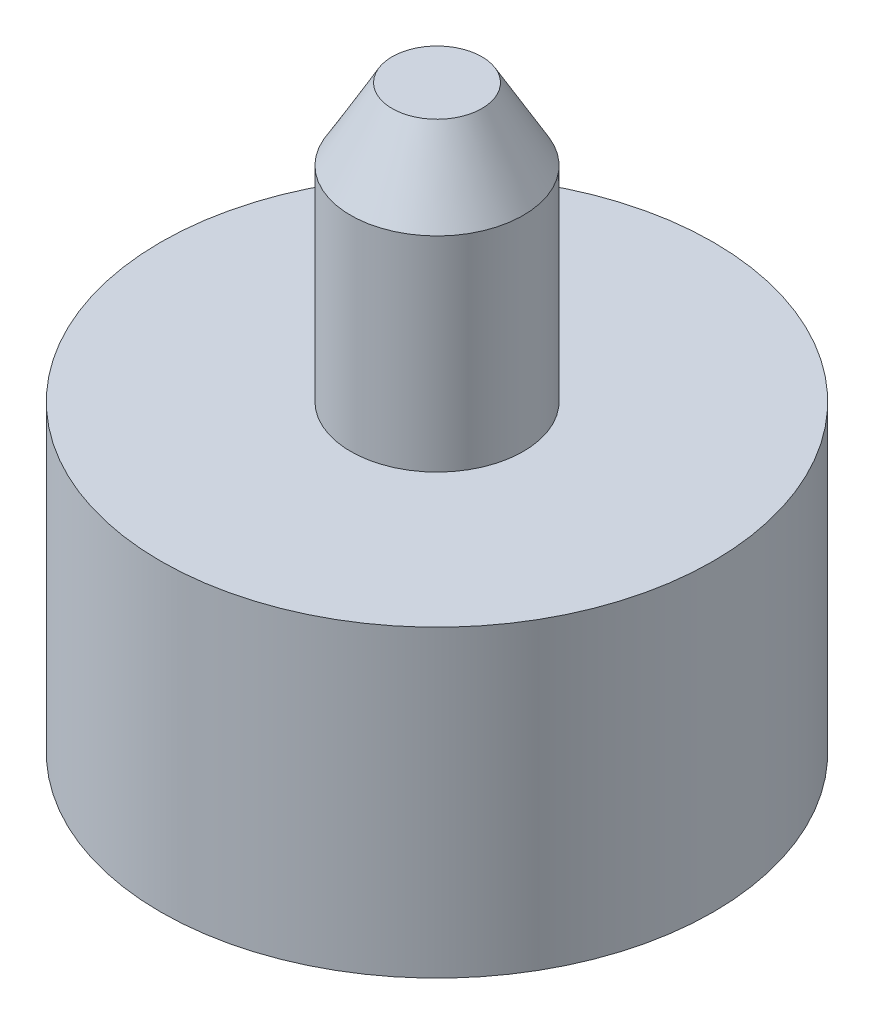
SolidWorks part; units mm, degrees
ref_plane "前视基准面" through (0, 0, 0) normal (0, 0, 1) x (1, 0, 0)
ref_plane "上视基准面" through (0, 0, 0) normal (0, 1, 0) x (1, 0, 0)
ref_plane "右视基准面" through (0, 0, 0) normal (1, 0, 0) x (0, 0, -1)
sketch "草图1" plane through (0, 0, 0) normal (0, 1, 0) x (1, 0, 0)
  circle A0 centre (0, 0) radius 40
  dimension "D1" = 80
extrude "凸台-拉伸1" add sketch "草图1" along normal blind 44
sketch "草图2" plane through (0, 0, 0) normal (0, 0, 1) x (1, 0, 0)
  line L0 (0, 44) -> (0, -18.1884)
  line L1 (40, 44) -> (-40, 44) construction
sketch "草图3" plane through (0, 0, 0) normal (0, -1, 0) x (1, 0, 0)
  circle A0 centre (0, 0) radius 12.5
  dimension "D1" = 25
extrude "凸台-拉伸2" add sketch "草图3" against normal blind 84
chamfer "倒角1" distance 6 angle 60 1 edges at (0, 84, -12.5)
